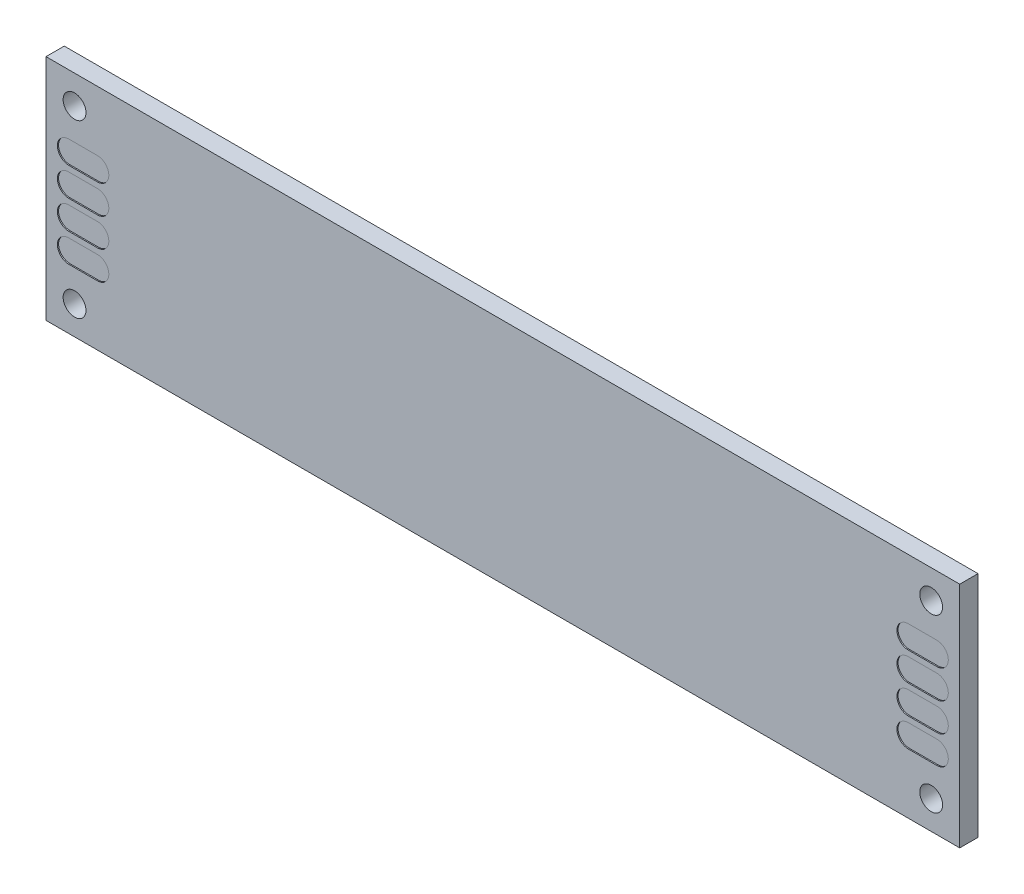
SolidWorks part; units mm, degrees
ref_plane "Спереди" through (0, 0, 0) normal (0, 0, 1) x (1, 0, 0)
ref_plane "Сверху" through (0, 0, 0) normal (0, 1, 0) x (1, 0, 0)
ref_plane "Справа" through (0, 0, 0) normal (1, 0, 0) x (0, 0, -1)
sketch "Эскиз1" plane through (0, 0, 0) normal (0, 0, 1) x (1, 0, 0)
  line L1 (-40, 10) -> (40, 10)
  line L2 (-40, 10) -> (-40, -10)
  line L3 (-40, -10) -> (40, -10)
  line L4 (40, 10) -> (40, -10)
  line L5 (-40, 10) -> (40, -10) construction
  line L6 (-40, -10) -> (40, 10) construction
  line L7 (-37.5, 7.5) -> (37.5, 7.5) construction
  line L8 (-37.5, 7.5) -> (-37.5, -7.5) construction
  line L9 (-37.5, -7.5) -> (37.5, -7.5) construction
  line L10 (37.5, 7.5) -> (37.5, -7.5) construction
  line L11 (-37.5, 7.5) -> (37.5, -7.5) construction
  line L12 (-37.5, -7.5) -> (37.5, 7.5) construction
  circle A0 centre (-37.5, 7.5) radius 1
  circle A1 centre (-37.5, -7.5) radius 1
  circle A2 centre (37.5, -7.5) radius 1
  circle A3 centre (37.5, 7.5) radius 1
  point P0 (0, 0)
  point P6 (0, 0)
  dimension "D5" = 2
  dimension "D1" = 20
  dimension "D2" = 80
  dimension "D3" = 15
  dimension "D4" = 75
extrude "Бобышка-Вытянуть1" add sketch "Эскиз1" along normal blind 1.6
sketch "Эскиз2" plane through (0, 0, 1.6) normal (0, 0, 1) x (1, 0, 0)
  line L0 (-38, -3.75) -> (-35.5, -3.75) construction
  line L1 (-38, -2.75) -> (-35.5, -2.75)
  line L2 (-38, -4.75) -> (-35.5, -4.75)
  line L3 (-38, -1.25) -> (-35.5, -1.25) construction
  line L4 (-38, -0.25) -> (-35.5, -0.25)
  line L5 (-38, -2.25) -> (-35.5, -2.25)
  line L6 (-38, 1.25) -> (-35.5, 1.25) construction
  line L7 (-38, 2.25) -> (-35.5, 2.25)
  line L8 (-38, 0.25) -> (-35.5, 0.25)
  line L9 (-40, 0) -> (40, 0) construction
  line L10 (-40, 10) -> (-40, -10) construction
  line L11 (40, -10) -> (40, 10) construction
  line L12 (0, 10) -> (0, -10) construction
  line L13 (40, 10) -> (-40, 10) construction
  line L14 (-40, -10) -> (40, -10) construction
  line L15 (38, -3.75) -> (35.5, -3.75) construction
  line L18 (38, -2.75) -> (35.5, -2.75)
  line L21 (38, -4.75) -> (35.5, -4.75)
  line L24 (-38, 3.75) -> (-35.5, 3.75) construction
  line L25 (-38, 4.75) -> (-35.5, 4.75)
  line L26 (-38, 2.75) -> (-35.5, 2.75)
  line L27 (38, -1.25) -> (35.5, -1.25) construction
  line L28 (38, -0.25) -> (35.5, -0.25)
  line L29 (38, -2.25) -> (35.5, -2.25)
  line L30 (38, 1.25) -> (35.5, 1.25) construction
  line L31 (38, 2.25) -> (35.5, 2.25)
  line L32 (38, 0.25) -> (35.5, 0.25)
  line L33 (38, 3.75) -> (35.5, 3.75) construction
  line L34 (38, 4.75) -> (35.5, 4.75)
  line L35 (38, 2.75) -> (35.5, 2.75)
  arc A0 (-38, -2.75) -> (-38, -4.75) centre (-38, -3.75) ccw
  arc A1 (-35.5, -4.75) -> (-35.5, -2.75) centre (-35.5, -3.75) ccw
  arc A2 (-38, -0.25) -> (-38, -2.25) centre (-38, -1.25) ccw
  arc A3 (-35.5, -2.25) -> (-35.5, -0.25) centre (-35.5, -1.25) ccw
  arc A4 (-38, 2.25) -> (-38, 0.25) centre (-38, 1.25) ccw
  arc A5 (-35.5, 0.25) -> (-35.5, 2.25) centre (-35.5, 1.25) ccw
  arc A12 (-38, 4.75) -> (-38, 2.75) centre (-38, 3.75) ccw
  arc A13 (-35.5, 2.75) -> (-35.5, 4.75) centre (-35.5, 3.75) ccw
  arc A14 (38, -2.75) -> (38, -4.75) centre (38, -3.75) cw
  arc A15 (35.5, -4.75) -> (35.5, -2.75) centre (35.5, -3.75) cw
  arc A16 (38, -0.25) -> (38, -2.25) centre (38, -1.25) cw
  arc A17 (35.5, -2.25) -> (35.5, -0.25) centre (35.5, -1.25) cw
  arc A18 (38, 2.25) -> (38, 0.25) centre (38, 1.25) cw
  arc A19 (35.5, 0.25) -> (35.5, 2.25) centre (35.5, 1.25) cw
  arc A20 (38, 4.75) -> (38, 2.75) centre (38, 3.75) cw
  arc A21 (35.5, 2.75) -> (35.5, 4.75) centre (35.5, 3.75) cw
  point P2 (-36.75, -3.75)
  point P9 (-36.75, -1.25)
  point P17 (-36.75, 1.25)
  point P36 (36.75, -3.75)
  point P43 (36.75, -1.25)
  point P50 (36.75, 1.25)
  point P56 (-36.75, 3.75)
  point P61 (0, 0)
  point P64 (36.75, 3.75)
  dimension "D2" = 2.5
  dimension "D3" = 2.5
  dimension "D4" = 2
  dimension "D5" = 3.25
  dimension "D6" = 0.25
  dimension "D1" = 4
extrude "Вырез-Вытянуть1" cut sketch "Эскиз2" against normal blind 0.1
sketch "Эскиз3" plane through (0, 0, 0) normal (0, 0, -1) x (-1, 0, 0)
  line L3 (38, -0.25) -> (35.5, -0.25)
  line L7 (35.5, -2.25) -> (38, -2.25)
  line L11 (38, -0.25) -> (35.5, -0.25)
  line L15 (35.5, -2.25) -> (38, -2.25)
  line L19 (38, -2.75) -> (35.5, -2.75)
  line L23 (35.5, -4.75) -> (38, -4.75)
  line L26 (38, -2.75) -> (35.5, -2.75)
  line L27 (35.5, -4.75) -> (38, -4.75)
  line L28 (38, 2.25) -> (35.5, 2.25)
  line L29 (35.5, 0.25) -> (38, 0.25)
  line L30 (38, 2.25) -> (35.5, 2.25)
  line L31 (35.5, 0.25) -> (38, 0.25)
  line L32 (-35.5, -0.25) -> (-38, -0.25)
  line L33 (-38, -2.25) -> (-35.5, -2.25)
  line L34 (-35.5, -0.25) -> (-38, -0.25)
  line L35 (-38, -2.25) -> (-35.5, -2.25)
  line L36 (-35.5, -2.75) -> (-38, -2.75)
  line L37 (-38, -4.75) -> (-35.5, -4.75)
  line L38 (-35.5, -2.75) -> (-38, -2.75)
  line L39 (-38, -4.75) -> (-35.5, -4.75)
  line L40 (-35.5, 2.25) -> (-38, 2.25)
  line L41 (-38, 0.25) -> (-35.5, 0.25)
  line L42 (-35.5, 2.25) -> (-38, 2.25)
  line L43 (-38, 0.25) -> (-35.5, 0.25)
  line L44 (38, 4.75) -> (35.5, 4.75)
  line L45 (35.5, 2.75) -> (38, 2.75)
  line L46 (38, 4.75) -> (35.5, 4.75)
  line L47 (35.5, 2.75) -> (38, 2.75)
  line L48 (-35.5, 4.75) -> (-38, 4.75)
  line L49 (-38, 2.75) -> (-35.5, 2.75)
  line L50 (-35.5, 4.75) -> (-38, 4.75)
  line L51 (-38, 2.75) -> (-35.5, 2.75)
  arc A26 (35.5, -0.25) -> (35.5, -2.25) centre (35.5, -1.25) ccw
  arc A27 (38, -2.25) -> (38, -0.25) centre (38, -1.25) ccw
  arc A28 (35.5, -0.25) -> (35.5, -2.25) centre (35.5, -1.25) ccw
  arc A29 (38, -2.25) -> (38, -0.25) centre (38, -1.25) ccw
  arc A30 (35.5, -2.75) -> (35.5, -4.75) centre (35.5, -3.75) ccw
  arc A31 (38, -4.75) -> (38, -2.75) centre (38, -3.75) ccw
  arc A32 (35.5, -2.75) -> (35.5, -4.75) centre (35.5, -3.75) ccw
  arc A33 (38, -4.75) -> (38, -2.75) centre (38, -3.75) ccw
  arc A34 (35.5, 2.25) -> (35.5, 0.25) centre (35.5, 1.25) ccw
  arc A35 (38, 0.25) -> (38, 2.25) centre (38, 1.25) ccw
  arc A36 (35.5, 2.25) -> (35.5, 0.25) centre (35.5, 1.25) ccw
  arc A37 (38, 0.25) -> (38, 2.25) centre (38, 1.25) ccw
  arc A38 (-35.5, -2.25) -> (-35.5, -0.25) centre (-35.5, -1.25) ccw
  arc A39 (-38, -0.25) -> (-38, -2.25) centre (-38, -1.25) ccw
  arc A40 (-35.5, -2.25) -> (-35.5, -0.25) centre (-35.5, -1.25) ccw
  arc A41 (-38, -0.25) -> (-38, -2.25) centre (-38, -1.25) ccw
  arc A42 (-35.5, -4.75) -> (-35.5, -2.75) centre (-35.5, -3.75) ccw
  arc A43 (-38, -2.75) -> (-38, -4.75) centre (-38, -3.75) ccw
  arc A44 (-35.5, -4.75) -> (-35.5, -2.75) centre (-35.5, -3.75) ccw
  arc A45 (-38, -2.75) -> (-38, -4.75) centre (-38, -3.75) ccw
  arc A46 (-35.5, 0.25) -> (-35.5, 2.25) centre (-35.5, 1.25) ccw
  arc A47 (-38, 2.25) -> (-38, 0.25) centre (-38, 1.25) ccw
  arc A48 (-35.5, 0.25) -> (-35.5, 2.25) centre (-35.5, 1.25) ccw
  arc A49 (-38, 2.25) -> (-38, 0.25) centre (-38, 1.25) ccw
  arc A50 (35.5, 4.75) -> (35.5, 2.75) centre (35.5, 3.75) ccw
  arc A51 (38, 2.75) -> (38, 4.75) centre (38, 3.75) ccw
  arc A52 (35.5, 4.75) -> (35.5, 2.75) centre (35.5, 3.75) ccw
  arc A53 (38, 2.75) -> (38, 4.75) centre (38, 3.75) ccw
  arc A54 (-35.5, 2.75) -> (-35.5, 4.75) centre (-35.5, 3.75) ccw
  arc A55 (-38, 4.75) -> (-38, 2.75) centre (-38, 3.75) ccw
  arc A56 (-35.5, 2.75) -> (-35.5, 4.75) centre (-35.5, 3.75) ccw
  arc A57 (-38, 4.75) -> (-38, 2.75) centre (-38, 3.75) ccw
  dimension "D1" = 0
  dimension "D2" = 0
  dimension "D3" = 0
  dimension "D4" = 0
  dimension "D5" = 0
  dimension "D6" = 0
  dimension "D7" = 0
  dimension "D8" = 0
extrude "Вырез-Вытянуть2" cut sketch "Эскиз3" against normal blind 0.1
